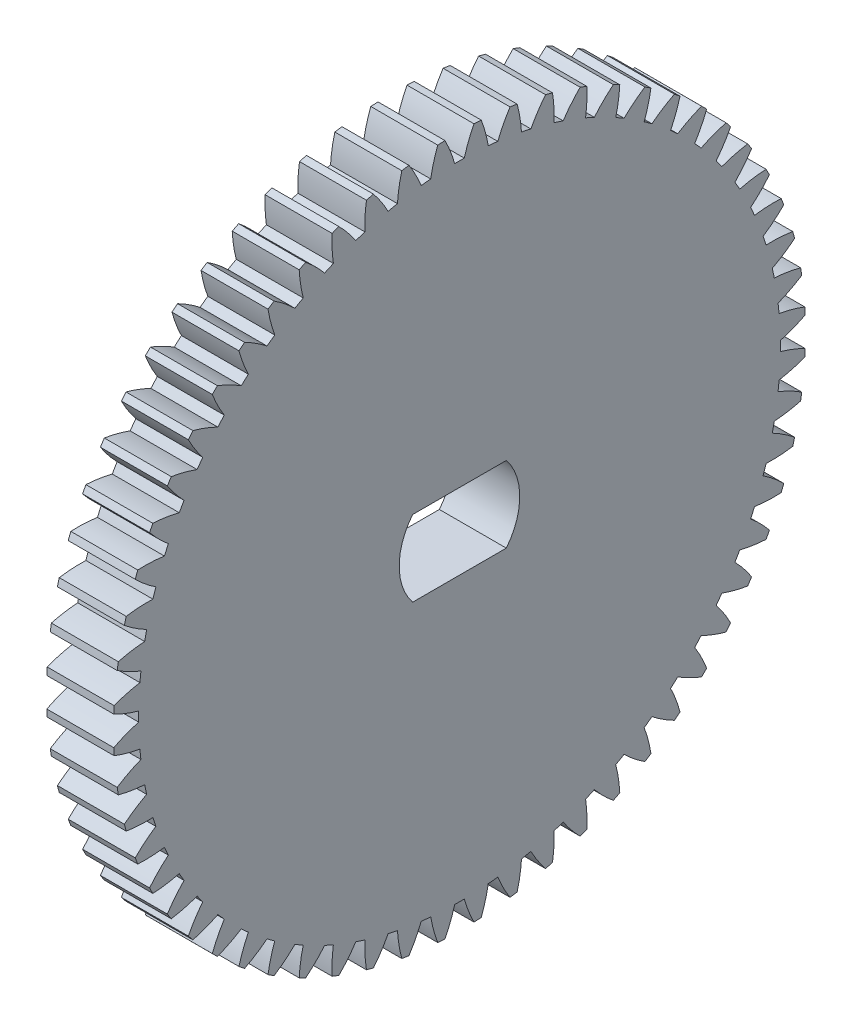
SolidWorks part; units mm, degrees
ref_plane "Plane1" through (0, 0, 0) normal (0, 0, 1) x (1, 0, 0)
ref_plane "Plane2" through (0, 0, 0) normal (0, 1, 0) x (1, 0, 0)
ref_plane "Plane3" through (0, 0, 0) normal (1, 0, 0) x (0, 0, -1)
sketch "HoldingSke" plane through (0, 0, 0) normal (0, 1, 0) x (1, 0, 0)
  line L0 (0, 0) -> (1, -1.7321)
  line L1 (-15, 0) -> (100, 0) construction
  line L2 (0, 0) -> (-2.1039, 2.3779)
  line L3 (0, 0) -> (-11.863, 4.5341)
  line L4 (0, 0) -> (4.318, 7.479)
  line L5 (0, 0) -> (-46.8476, -17.4728)
  line L6 (0, 0) -> (-2.4869, -1.6779)
  line L7 (-2.1039, 2.3779) -> (8.6586, 51.2059)
  line L8 (-76.2, 54.61) -> (-76.1, 54.61)
  line L9 (-71.009, 38.7566) -> (-53.1078, 45.2721)
  line L10 (-76.2, 71.12) -> (104.1128, 71.12)
  line L11 (0, 0) -> (-3, 0)
  line L12 (-76.2, 101.6) -> (-76.181, 101.6)
  line L13 (24.9733, 27.94) -> (52.9518, 28.4284)
  line L14 (24.9733, 27.94) -> (24.9743, 27.94)
  line L15 (24.9733, 27.94) -> (100.4006, 29.5858)
  line L16 (-63.627, -0.5) -> (-12.827, -0.5)
  circle A0 centre (0, 0) radius 0.5
  circle A1 centre (0, 0) radius 14.374
  circle A2 centre (0, 0) radius 37.5
  circle A3 centre (0, 0) radius 0.5
  dimension "MHD" = 28.748
  dimension "Hub_dia" = 75
  dimension "Bore" = 1
  dimension "MBD" = 1
  dimension "Num_teeth" = 60
  dimension "Pitch" = 2
  dimension "Overall_len" = 50
  dimension "Show_teeth" = 60
  dimension "Thickness" = 3
  dimension "OAL" = 50.0001
  dimension "T_dim" = 0.1
  dimension "Ap" = 20
  dimension "H" = 19.05
  dimension "Pitch_radius" = 180.3128
  dimension "Width" = 3
  dimension "Backlash" = 0.019
  dimension "Addendum_fac" = 1
  dimension "Dedendum_fac" = 1.25
  dimension "Clearance_fac" = 0.25
  dimension "Dedendum_add" = 0.001
  dimension "Module" = 0.5
sketch "BasProSke" plane through (0, 0, 0) normal (0, 1, 0) x (1, 0, 0)
  line L0 (-10, 0) -> (60, 0) construction
  line L1 (0, 0) -> (0, 15.5)
  line L2 (0, 0) -> (3, 0)
  line L3 (3, 0) -> (3, 15.5)
  line L4 (3, 15.5) -> (0, 15.5)
  dimension "Thickness" = 3
  dimension "Diameter" = 31
revolve "Base-Revolve" add sketch "BasProSke" angle 360 about L0
sketch "TooCutSke" plane through (0, 0, 0) normal (1, 0, 0) x (0, 0, -1)
  line L1 (0, 0) -> (0, 107) construction
  line L2 (0, 0) -> (-0.4259, 14.994) construction
  line L3 (0, 0) -> (-1.5696, 29.9503) construction
  line L4 (-0.4259, 14.994) -> (-0.7848, 14.9751) construction
  arc A0 (0.2149, 14.3724) -> (-0.2149, 14.3724) centre (0, 0) ccw
  arc A1 (0.6627, 15.5112) -> (-0.6627, 15.5112) centre (0, 0) ccw
  circle A2 centre (0, 0) radius 15 construction
  circle A3 centre (0, 0) radius 14.0954 construction
  arc A4 (-0.2149, 14.3724) -> (-0.6627, 15.5112) centre (-5.9936, 12.7576) ccw
  arc A5 (0.6627, 15.5112) -> (0.2149, 14.3724) centre (5.9936, 12.7576) ccw
  dimension "Root_dia" = 28.748
  dimension "Overcut_dia" = 31.0508
  dimension "Pitch_dia" = 30
  dimension "Base_dia" = 28.1908
  dimension "Flank_rad" = 6
  dimension "Half_ang" = 3
  dimension "Half_CT" = 0.3594
extrude "ToothCut" cut sketch "TooCutSke" along normal through all
fillet "Breaks" [suppressed] radius 0.01
fillet "RootFillets" [suppressed] radius 0.126
pattern_circular "TeethCuts" count 60 every 6 about axis through (-10, 0, 0) along (1, 0, 0) of "ToothCut", "RootFillets", "Breaks"
sketch "HubNeaOneSke" plane through (0, 0, 0) normal (-1, 0, 0) x (0, 0, 1)
  circle A0 centre (0, 0) radius 14.374
  dimension "Diameter" = 28.748
extrude "HubNearOne" [suppressed] add sketch "HubNeaOneSke" along normal blind 47.0001
sketch "HubNeaBotSke" plane through (0, 0, 0) normal (-1, 0, 0) x (0, 0, 1)
  circle A0 centre (0, 0) radius 14.374
  dimension "Diameter" = 28.748
extrude "HubNearBoth" [suppressed] add sketch "HubNeaBotSke" along normal blind 23.5
ref_plane "FarPln" through (3, 0, 0) normal (1, 0, 0) x (0, 0, -1)
sketch "HubFarSke" plane through (3, 0, 0) normal (1, 0, 0) x (0, 0, -1)
  circle A0 centre (0, 0) radius 14.374
  dimension "Diameter" = 28.748
extrude "HubFar" [suppressed] add sketch "HubFarSke" along normal blind 23.5
sketch "BorSke" plane through (0, 0, 0) normal (1, 0, 0) x (0, 0, -1)
  circle A0 centre (0, 0) radius 0.5
  dimension "Diameter" = 1
extrude "Bore" cut sketch "BorSke" along normal mid plane 100.0001
sketch "KeySke" plane through (0, 0, 0) normal (1, 0, 0) x (0, 0, -1)
  line L0 (-0.05, 0) -> (-0.05, 0.6)
  line L1 (-0.05, 0.6) -> (0.05, 0.6)
  line L2 (0.05, 0.6) -> (0.05, 0)
  line L3 (0, 0) -> (0, 34) construction
  line L4 (-0.05, 0) -> (0.05, 0)
  dimension "Offset" = 0.6
  dimension "Width" = 0.1
extrude "Keyway" [suppressed] cut sketch "KeySke" along normal mid plane 100.0001
pattern_circular "Keyway2" [suppressed] count 2 every 90 about axis through (-10, 0, 0) along (1, 0, 0)
sketch "Sketch1" plane through (3, 0, 0) normal (1, 0, 0) x (0, 0, -1)
  line L0 (-2, 1.5) -> (2, 1.5)
  line L1 (2, -1.5) -> (-2, -1.5)
  line L2 (2.0976, -1.7) -> (-2.0976, -1.7)
  line L3 (-2.0976, 1.7) -> (2.0976, 1.7)
  arc A0 (-2, 1.5) -> (-2, -1.5) centre (0, 0) ccw
  arc A1 (2, -1.5) -> (2, 1.5) centre (0, 0) ccw
  arc A2 (-2.0976, 1.7) -> (-2.0976, -1.7) centre (0, 0) ccw
  arc A3 (2.0976, -1.7) -> (2.0976, 1.7) centre (0, 0) ccw
  dimension "D1" = 3
  dimension "D3" = 5
  dimension "D2" = 1.5
  dimension "D4" = 0.2
extrude "Cut-Extrude1" cut sketch "Sketch1" against normal blind 10 contours L1 A1 L0 A0 | L2 A3 L3 A2 A1 L1 A0 L0
equation "' \"Module@HoldingSke\" = 6.35"
equation "' \"Num_teeth@HoldingSke\" = 12"
equation "' \"Ap@HoldingSke\" =  20"
equation "' \"Ap@HoldingSke\" = 20"
equation "' \"Width@HoldingSke\" = 0.5 * 25.4"
equation "' \"Hub_dia@HoldingSke\"= 1 * 25.4"
equation "' \"Hub_dia@HoldingSke\" = 1 * 25.4"
equation "' \"Overall_len@HoldingSke\" = 1.0 * 25.4"
equation "' \"Bore@HoldingSke\" = 0.75 * 25.4"
equation "' \"T_dim@HoldingSke\" = 0.1 * 25.4"
equation "' \"Width@KeySke\" = 0.25 * 25.4"
equation "' \"Show_teeth@HoldingSke\" = 13"
equation "' \"Backlash@HoldingSke\" = 0.009 * 25.4"
equation "' \"Addendum_fac@HoldingSke\" = 1.0"
equation "' \"Dedendum_fac@HoldingSke\" = 1.25"
equation "' \"Dedendum_add@HoldingSke\" = 0.00005 * 25.4"
equation "' \"Clearance_fac@HoldingSke\" = 0.25"
equation "\"Pitch@HoldingSke\" = 1 / \"Module@HoldingSke\""
equation "\"Overcut_dia@TooCutSke\" = (\"Num_teeth@HoldingSke\" + 2 * \"Addendum_fac@HoldingSke\") / \"Pitch@HoldingSke\" + 0.002 * 25.4"
equation "\"Pitch_dia@TooCutSke\" = \"Num_teeth@HoldingSke\" / \"Pitch@HoldingSke\""
equation "\"Base_dia@TooCutSke\" = \"Num_teeth@HoldingSke\" / \"Pitch@HoldingSke\" * cos((\"Ap@HoldingSke\"  * 3.14159265 / 180))"
equation "\"Root_dia@TooCutSke\" = (\"Num_teeth@HoldingSke\" + 2) / \"Pitch@HoldingSke\" - 2 * (\"Addendum_fac@HoldingSke\" + \"Dedendum_fac@HoldingSke\") / \"Pitch@HoldingSke\" - \"Dedendum_add@HoldingSke\" * 2"
equation "\"Half_ang@TooCutSke\" = 180 / \"Num_teeth@HoldingSke\""
equation "\"Half_CT@TooCutSke\" = \"Num_teeth@HoldingSke\" / \"Pitch@HoldingSke\" * sin((3.14159265 / 2 / \"Num_teeth@HoldingSke\")) / 2 - 7 * \"Backlash@HoldingSke\" / 4"
equation "\"Flank_rad@TooCutSke\" = \"Num_teeth@HoldingSke\" / \"Pitch@HoldingSke\" / 5"
equation "\"Radius@RootFillets\" = \"Clearance_fac@HoldingSke\" / \"Pitch@HoldingSke\" + \"Dedendum_add@HoldingSke\""
equation "\"Break_rad@Breaks\" = 0.02 / \"Pitch@HoldingSke\""
equation "\"Thickness@HoldingSke\" = \"Width@HoldingSke\""
equation "\"OAL@HoldingSke\" = \"Thickness@HoldingSke\""
equation "\"MHD@HoldingSke\" = (\"Num_teeth@HoldingSke\" + 2) / \"Pitch@HoldingSke\" - 2 * (\"Addendum_fac@HoldingSke\" + \"Dedendum_fac@HoldingSke\")  / \"Pitch@HoldingSke\" - \"Dedendum_add@HoldingSke\" * 2"
equation "\"MBD@HoldingSke\" = (\"Num_teeth@HoldingSke\" + 2) / \"Pitch@HoldingSke\" - 2 * (\"Addendum_fac@HoldingSke\" + \"Dedendum_fac@HoldingSke\")  / \"Pitch@HoldingSke\" - \"Dedendum_add@HoldingSke\" * 2 - 0.002 * 25.4"
equation "\"MHD@HoldingSke\" = ((sgn( \"MHD@HoldingSke\" - \"Hub_dia@HoldingSke\" )-1)*( \"MHD@HoldingSke\" - \"Hub_dia@HoldingSke\" ))/-2+ \"Hub_dia@HoldingSke\""
equation "\"MBD@HoldingSke\" = ((sgn( \"MBD@HoldingSke\" - \"Bore@HoldingSke\" )-1)*( \"MBD@HoldingSke\" - \"Bore@HoldingSke\" ))/-2+ \"Bore@HoldingSke\""
equation "\"OAL@HoldingSke\" = ((sgn( \"OAL@HoldingSke\" - \"Overall_len@HoldingSke\" )+1)*( \"OAL@HoldingSke\" - \"Overall_len@HoldingSke\" ))/2 + \"Overall_len@HoldingSke\" + 0.000002 * 25.4"
equation "\"Num_teeth@TeethCuts\" = int( \"Show_teeth@HoldingSke\" ) + 1"
equation "\"Num_teeth@TeethCuts\" = ((sgn( \"Num_teeth@TeethCuts\" - \"Num_teeth@HoldingSke\" )-1)*( \"Num_teeth@TeethCuts\" - \"Num_teeth@HoldingSke\" ))/-2+ \"Num_teeth@HoldingSke\""
equation "\"Num_teeth@TeethCuts\" = ((sgn( \"Num_teeth@TeethCuts\" - 2.0)+1)*( \"Num_teeth@TeethCuts\" - 2.0))/2 +2.0"
equation "\"Angle@TeethCuts\" = 360.0 / \"Num_teeth@HoldingSke\""
equation "\"Diameter@BasProSke\" = (\"Num_teeth@HoldingSke\" + 2 * \"Addendum_fac@HoldingSke\") / \"Pitch@HoldingSke\""
equation "\"Thickness@BasProSke\"  = \"Thickness@HoldingSke\""
equation "' \"Fillet_rad@BasProSke\" =  \"Thickness@HoldingSke\" * 0.05"
equation "' \"Fillet_rad@BasProSke\" = \"Thickness@HoldingSke\" * 0.05"
equation "\"MHD@HoldingSke\" = ((sgn( \"MHD@HoldingSke\" - \"Root_dia@TooCutSke\" )-1)*( \"MHD@HoldingSke\" - \"Root_dia@TooCutSke\" ))/-2+ \"Root_dia@TooCutSke\""
equation "\"Diameter@HubNeaOneSke\" = \"MHD@HoldingSke\""
equation "\"Length@HubNearOne\" = \"OAL@HoldingSke\" - \"Thickness@BasProSke\""
equation "\"Diameter@HubNeaBotSke\" = \"MHD@HoldingSke\""
equation "\"Length@HubNearBoth\" = ( \"OAL@HoldingSke\" - \"Thickness@BasProSke\" ) / 2.0"
equation "\"Thickness@FarPln\" = \"Thickness@BasProSke\""
equation "\"Diameter@HubFarSke\" = \"MHD@HoldingSke\""
equation "\"Length@HubFar\" = ( \"OAL@HoldingSke\" - \"Thickness@BasProSke\" ) / 2.0"
equation "\"Diameter@BorSke\" = \"MBD@HoldingSke\""
equation "\"D1@Bore\" = \"OAL@HoldingSke\" * 2.0"
equation "\"D1@Keyway\" = \"OAL@HoldingSke\" * 2.0"
equation "\"Offset@KeySke\" = \"T_dim@HoldingSke\" + \"MBD@HoldingSke\" / 2.0"
